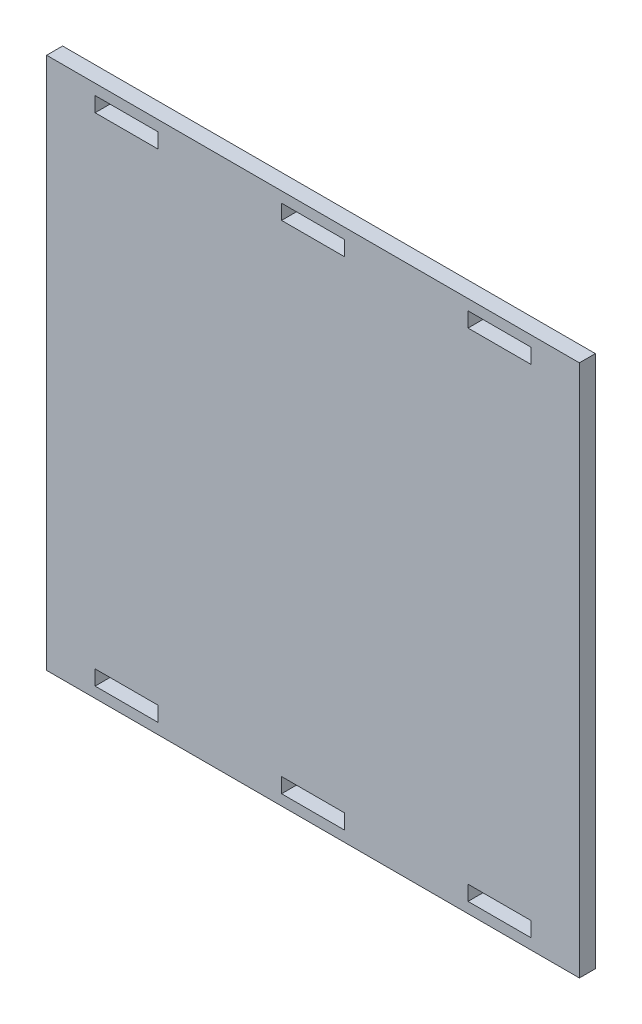
SolidWorks part; units mm, degrees
ref_plane "Спереди" through (0, 0, 0) normal (0, 0, 1) x (1, 0, 0)
ref_plane "Сверху" through (0, 0, 0) normal (0, 1, 0) x (1, 0, 0)
ref_plane "Справа" through (0, 0, 0) normal (1, 0, 0) x (0, 0, -1)
sketch "Эскиз1" plane through (0, 0, 0) normal (0, 0, 1) x (1, 0, 0)
  line L0 (50, 0) -> (50, -12.7607) construction
  line L1 (0, 0) -> (100, 0)
  line L2 (0, 0) -> (0, 100)
  line L3 (0, 100) -> (100, 100)
  line L4 (100, 0) -> (100, 100)
  line L5 (9.1, 4.8) -> (20.9, 4.8)
  line L6 (9.1, 4.8) -> (9.1, 2)
  line L7 (9.1, 2) -> (20.9, 2)
  line L8 (20.9, 4.8) -> (20.9, 2)
  line L9 (9.1, 4.8) -> (20.9, 2) construction
  line L10 (9.1, 2) -> (20.9, 4.8) construction
  line L11 (0, 50) -> (100, 50) construction
  line L12 (15, 3.4) -> (15, 0) construction
  line L13 (44.1, 4.8) -> (44.1, 2)
  line L14 (44.1, 4.8) -> (55.9, 4.8)
  line L15 (55.9, 4.8) -> (55.9, 2)
  line L16 (44.1, 2) -> (55.9, 2)
  line L17 (79.1, 4.8) -> (79.1, 2)
  line L18 (79.1, 4.8) -> (90.9, 4.8)
  line L19 (90.9, 4.8) -> (90.9, 2)
  line L20 (79.1, 2) -> (90.9, 2)
  line L21 (50, 2) -> (50, 4.8) construction
  line L22 (79.1, 95.2) -> (90.9, 95.2)
  line L23 (90.9, 95.2) -> (90.9, 98)
  line L24 (79.1, 98) -> (90.9, 98)
  line L25 (79.1, 95.2) -> (79.1, 98)
  line L26 (44.1, 95.2) -> (55.9, 95.2)
  line L27 (55.9, 95.2) -> (55.9, 98)
  line L28 (44.1, 98) -> (55.9, 98)
  line L29 (44.1, 95.2) -> (44.1, 98)
  line L30 (9.1, 98) -> (20.9, 98)
  line L31 (20.9, 95.2) -> (20.9, 98)
  line L32 (9.1, 95.2) -> (20.9, 95.2)
  line L33 (9.1, 95.2) -> (9.1, 98)
  point P5 (15, 3.4)
  dimension "D1" = 100
  dimension "D2" = 100
  dimension "D3" = 2.8
  dimension "D4" = 11.8
  dimension "D5" = 2
  dimension "D6" = 35
  dimension "D8" = 35
  dimension "D7" = 3
extrude "Бобышка-Вытянуть1" add sketch "Эскиз1" against normal blind 3
